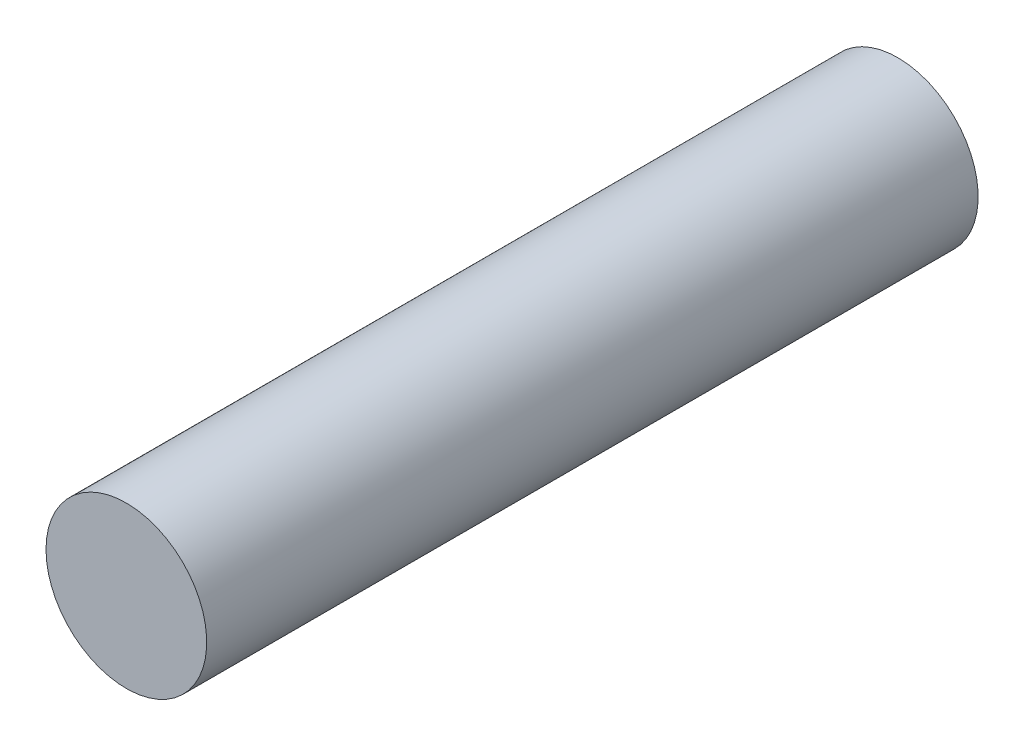
SolidWorks part; units mm, degrees
ref_plane "Front Plane" through (0, 0, 0) normal (0, 0, 1) x (1, 0, 0)
ref_plane "Top Plane" through (0, 0, 0) normal (0, 1, 0) x (1, 0, 0)
ref_plane "Right Plane" through (0, 0, 0) normal (1, 0, 0) x (0, 0, -1)
sketch "Sketch1" plane through (0, 0, 0) normal (0, 0, 1) x (1, 0, 0)
  line L1 (-15.875, 0) -> (15.875, 0) construction
  dimension "OD" = 31.75
sketch "Sketch2" plane through (0, 0, 0) normal (1, 0, 0) x (0, 0, -1)
  line L0 (76.2, 0) -> (-76.2, 0)
  point P4 (0, 0)
  dimension "Length" = 152.4
sketch "Sketch3" plane through (0, 0, 0) normal (0, 0, 1) x (1, 0, 0)
  circle A0 centre (0, 0) radius 15.875
extrude "Boss-Extrude1" add sketch "Sketch3" along normal up to vertex (76.2 mm away) and the other way up to vertex (76.2 mm away) up to point (0, 0, 76.2) other way up to point (0, 0, -76.2)
